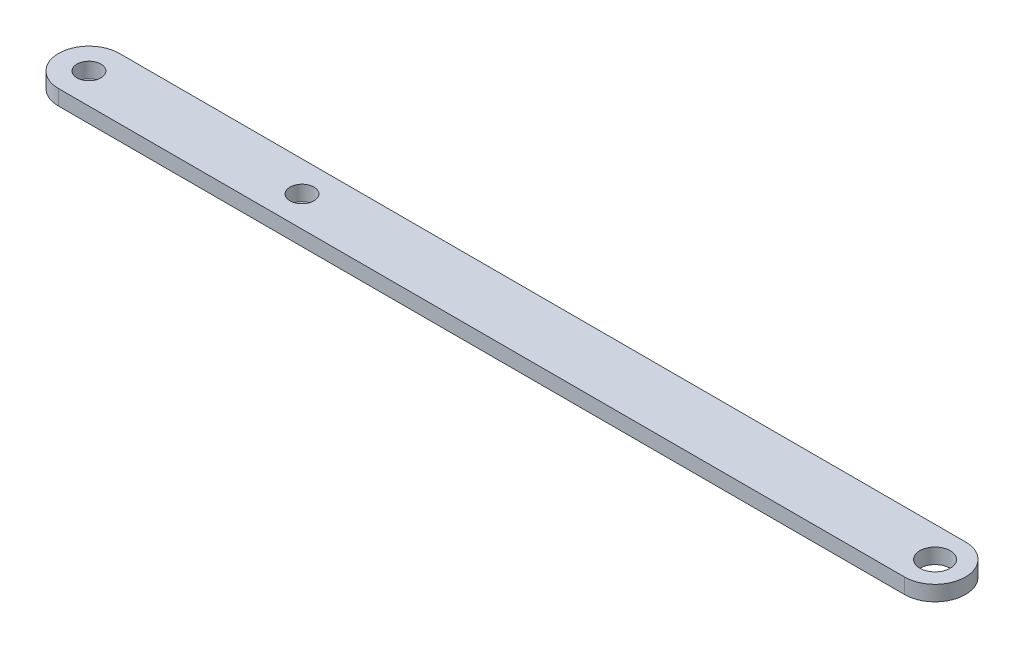
SolidWorks part; units mm, degrees
ref_plane "Front Plane" through (0, 0, 0) normal (0, 0, 1) x (1, 0, 0)
ref_plane "Top Plane" through (0, 0, 0) normal (0, 1, 0) x (1, 0, 0)
ref_plane "Right Plane" through (0, 0, 0) normal (1, 0, 0) x (0, 0, -1)
sketch "Sketch1" plane through (0, 0, 0) normal (0, 1, 0) x (1, 0, 0)
  line L0 (0, 0) -> (176.5478, 0) construction
  line L1 (0, 6.35) -> (176.5478, 6.35)
  line L2 (0, -6.35) -> (176.5478, -6.35)
  arc A0 (0, 6.35) -> (0, -6.35) centre (0, 0) ccw
  arc A1 (176.5478, -6.35) -> (176.5478, 6.35) centre (176.5478, 0) ccw
  circle A2 centre (0, 0) radius 2.5
  circle A3 centre (44.45, 0) radius 2.5
  circle A4 centre (176.5478, 0) radius 3.175
  point P3 (88.2739, 0)
  dimension "D2" = 6.35
  dimension "D3" = 5
  dimension "D4" = 6.35
  dimension "D1" = 176.5478
  dimension "D5" = 44.45
extrude "Boss-Extrude1" add sketch "Sketch1" along normal blind 3.175
